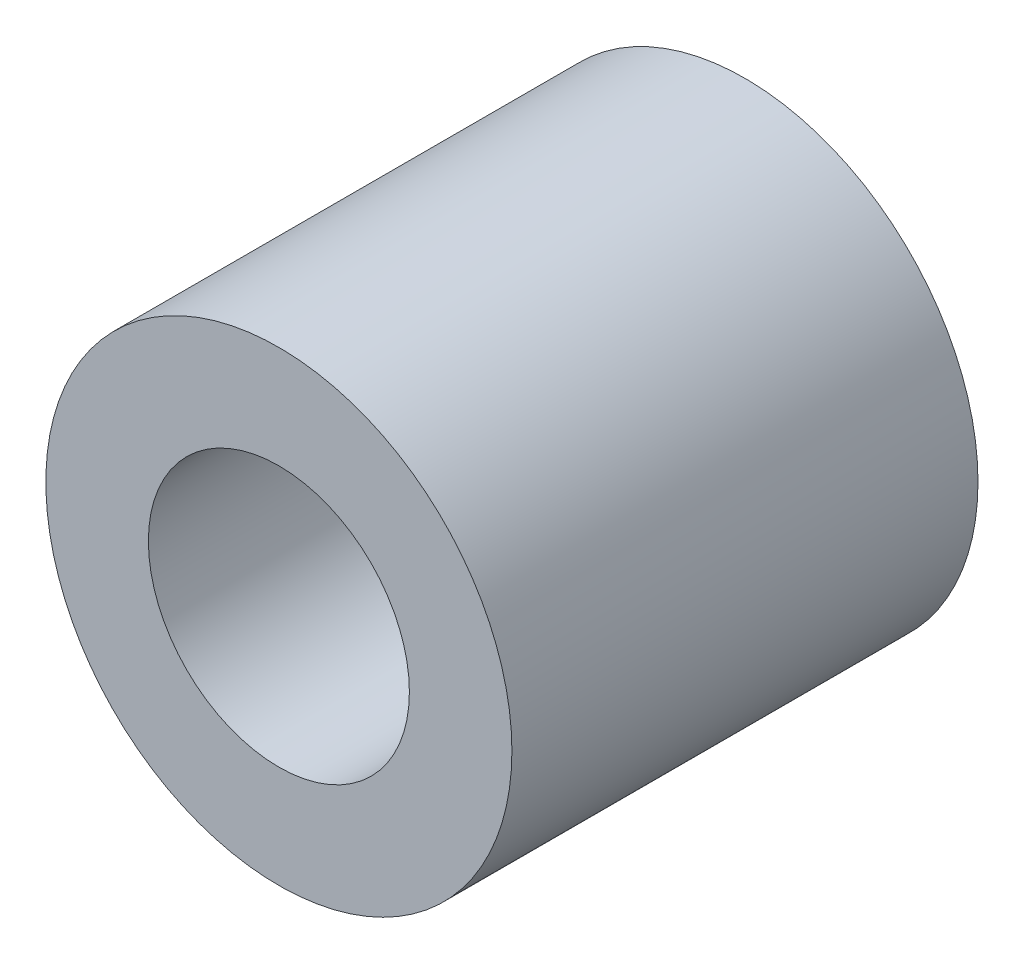
SolidWorks part; units mm, degrees
ref_plane "Front Plane" through (0, 0, 0) normal (0, 0, 1) x (1, 0, 0)
ref_plane "Top Plane" through (0, 0, 0) normal (0, 1, 0) x (1, 0, 0)
ref_plane "Right Plane" through (0, 0, 0) normal (1, 0, 0) x (0, 0, -1)
sketch "Sketch1" plane through (0, 0, 0) normal (0, 0, 1) x (1, 0, 0)
  circle A0 centre (0, 0) radius 3.175
  circle A1 centre (0, 0) radius 1.778
  dimension "OD" = 6.35
  dimension "ID" = 3.556
extrude "Extrude1" add sketch "Sketch1" along normal mid plane 6.35
sketch "Sketch2" plane through (0, 0, 0) normal (1, 0, 0) x (0, 0, -1)
  line L0 (-3.175, -1.778) -> (3.175, -1.778) construction
  line L3 (3.175, 1.778) -> (-3.175, 1.778) construction
  line L5 (-3.175, -1.778) -> (3.175, -1.778)
  line L6 (3.175, 1.778) -> (-3.175, 1.778)
sketch "Sketch4" plane through (0, 0, 3.175) normal (0, 0, 1) x (1, 0, 0)
  line L0 (0, 0) -> (-1.2572, 1.2572)
  line L1 (0, -2.1828) -> (0, 2.1828) construction
  circle A0 centre (0, 0) radius 1.778 construction
  dimension "D1" = 45
